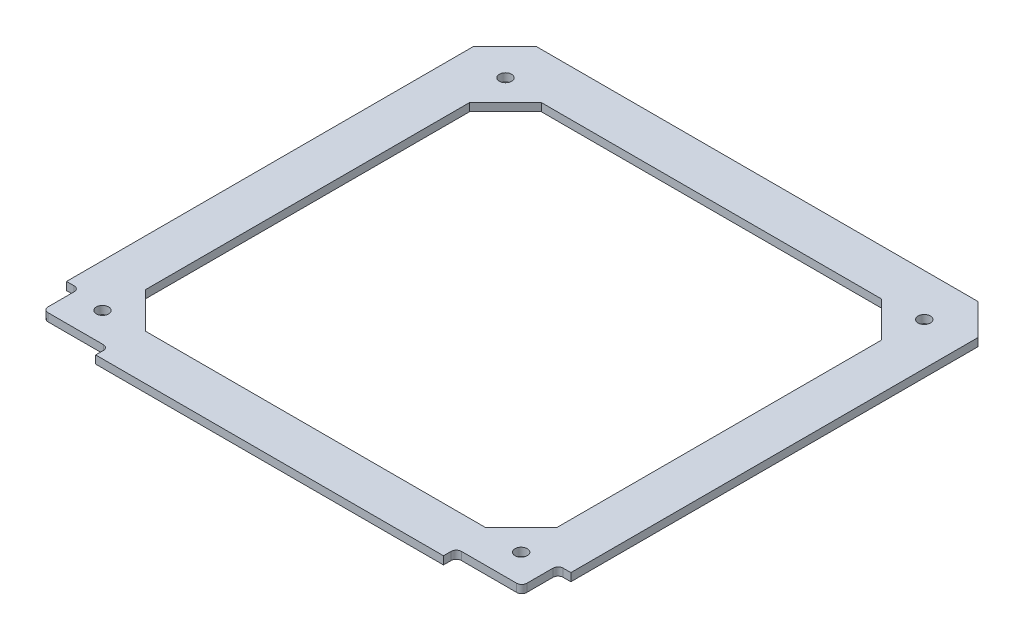
SolidWorks part; units mm, degrees
ref_plane "Front Plane" through (0, 0, 0) normal (0, 0, 1) x (1, 0, 0)
ref_plane "Top Plane" through (0, 0, 0) normal (0, 1, 0) x (1, 0, 0)
ref_plane "Right Plane" through (0, 0, 0) normal (1, 0, 0) x (0, 0, -1)
sketch "Sketch1" plane through (0, 0, 0) normal (0, 1, 0) x (1, 0, 0)
  line L0 (-49.3567, 41.6048) -> (-43.2567, 47.7048)
  line L1 (-34.0567, -47.5952) -> (33.9433, -47.5952)
  line L2 (-49.3567, -37.9952) -> (-49.3567, 41.6048)
  line L3 (-43.2567, 47.7048) -> (43.1433, 47.7048)
  line L4 (49.2433, -37.9952) -> (49.2433, 41.6048)
  line L5 (-49.3567, -47.5952) -> (49.2979, 47.5386) construction
  line L6 (-49.3567, 47.7048) -> (49.2433, -47.5952) construction
  line L7 (-0.0567, 0.0548) -> (-0.0567, 47.7048) construction
  line L8 (49.2433, 41.6048) -> (43.1433, 47.7048)
  line L9 (-46.8567, -44.0952) -> (-46.8567, -38.9952)
  line L10 (-45.8567, -45.0952) -> (-35.0567, -45.0952)
  line L11 (46.7433, -44.0952) -> (46.7433, -38.9952)
  line L12 (-49.3567, -37.9952) -> (-47.8567, -37.9952)
  line L13 (-34.0567, -47.5952) -> (-34.0567, -46.0952)
  line L14 (33.9433, -47.5952) -> (33.9433, -46.0952)
  line L15 (49.2433, -37.9952) -> (47.7433, -37.9952)
  line L16 (34.9433, -45.0952) -> (45.7433, -45.0952)
  line L17 (-46.8567, -45.0952) -> (-46.8567, 41.6048) construction
  line L18 (46.7433, -45.0952) -> (46.7433, 41.6048) construction
  line L20 (-46.8567, -45.0952) -> (46.7433, -45.0952) construction
  line L21 (-49.3567, -47.5952) -> (49.2433, -47.5952) construction
  line L22 (-49.3567, -47.5952) -> (-49.3567, 41.6048) construction
  line L23 (49.2433, -47.5952) -> (49.2433, 41.6048) construction
  arc A0 (47.7433, -37.9952) -> (46.7433, -38.9952) centre (47.7433, -38.9952) ccw
  arc A1 (34.9433, -45.0952) -> (33.9433, -46.0952) centre (34.9433, -46.0952) ccw
  arc A2 (-34.0567, -46.0952) -> (-35.0567, -45.0952) centre (-35.0567, -46.0952) ccw
  arc A3 (-46.8567, -38.9952) -> (-47.8567, -37.9952) centre (-47.8567, -38.9952) ccw
  arc A4 (46.7433, -44.0952) -> (45.7433, -45.0952) centre (45.7433, -44.0952) cw
  arc A5 (-45.8567, -45.0952) -> (-46.8567, -44.0952) centre (-45.8567, -44.0952) cw
  point P0 (0, 0)
  point P26 (46.7433, -37.9952)
  point P29 (33.9433, -45.0952)
  point P32 (-34.0567, -45.0952)
  point P35 (-46.8567, -37.9952)
  point P42 (-43.2567, 44.0048)
  point P43 (43.1433, 44.0048)
  dimension "D9" = 1
  dimension "D10" = 1
  dimension "D11" = 79.6
  dimension "D2" = 98.6
  dimension "D3" = 47.65
  dimension "D4" = 6.1
  dimension "D5" = 6.1
  dimension "D6" = 2.5
  dimension "D7" = 137.0517
  dimension "D8" = 15.3
  dimension "D12" = 49.3567
  dimension "D15" = 137.1279
extrude "Boss-Extrude1" add sketch "Sketch1" along normal blind 1.56
sketch "Sketch2" plane through (0, 1.56, 0) normal (0, 1, 0) x (1, 0, 0)
  line L0 (-40.2433, 31.7048) -> (-33.2433, 38.7048)
  line L1 (33.2433, -38.7048) -> (-33.2433, -38.7048)
  line L2 (40.2433, -31.7048) -> (40.2433, 31.7048)
  line L3 (33.2433, 38.7048) -> (-33.2433, 38.7048)
  line L4 (-40.2433, -31.7048) -> (-40.2433, 31.7048)
  line L5 (40.2433, -38.7048) -> (-40.2433, 38.7048) construction
  line L6 (40.2433, 38.7048) -> (-40.2433, -38.7048) construction
  line L7 (40.2433, 31.7048) -> (33.2433, 38.7048)
  line L8 (49.2433, -37.9952) -> (49.2433, 41.6048) construction
  line L9 (43.1433, 47.7048) -> (-43.2567, 47.7048) construction
  line L10 (33.2433, -38.7048) -> (40.2433, -31.7048)
  line L11 (-33.2433, -38.7048) -> (-40.2433, -31.7048)
  point P0 (0, 0)
  point P24 (-40.2433, 38.7048)
  point P27 (40.2433, 38.7048)
  point P30 (40.2433, -38.7048)
  point P33 (-40.2433, -38.7048)
  dimension "D1" = 9
  dimension "D2" = 9
extrude "Cut-Extrude1" cut sketch "Sketch2" against normal blind 1.56
sketch "Sketch3" plane through (0, 0, 0) normal (0, 1, 0) x (1, 0, 0)
  circle A0 centre (0, 0) radius 38.5
hole_wizard "M2 Clearance Hole1" positions "Sketch5" profile "Sketch4" hole size "M2" standard "ANSI Metric"
sketch "Sketch5" plane through (0, 1.56, 0) normal (0, 1, 0) x (1, 0, 0)
  line L1 (-46.75, -45) -> (46.75, -45) construction
  line L2 (-46.75, -45) -> (-46.75, 45) construction
  line L3 (-46.75, 45) -> (46.75, 45) construction
  line L4 (46.75, -45) -> (46.75, 45) construction
  line L5 (-46.75, -45) -> (46.75, 45) construction
  line L6 (-46.75, 45) -> (46.75, -45) construction
  point P0 (40.9295, 39.3974)
  point P2 (40.9295, -39.3974)
  point P4 (-40.9295, -39.3974)
  point P6 (-40.9295, 39.3974)
  point P11 (0, 0)
  dimension "D1" = 56.81
  dimension "D2" = 56.81
  dimension "D3" = 56.81
  dimension "D4" = 56.81
  dimension "D5" = 90
  dimension "D6" = 93.5
sketch "Sketch4" plane through (40.9295, 1.56, -39.3974) normal (1, 0, 0) x (0, 0, 1)
  line L0 (0, 0) -> (0, 38.821)
  line L1 (0, 38.821) -> (1.2, 38.1)
  line L2 (1.2, 38.1) -> (1.2, 0)
  line L5 (1.2, 0) -> (0, 0)
  line L10 (0, 38.821) -> (-1.2, 38.1) construction
  line L11 (0, -6.35) -> (0, 107.95) construction
  dimension "Hole Dia." = 2.4
  dimension "Hole Depth" = 38.1
  dimension "Drill Angle" = 118
